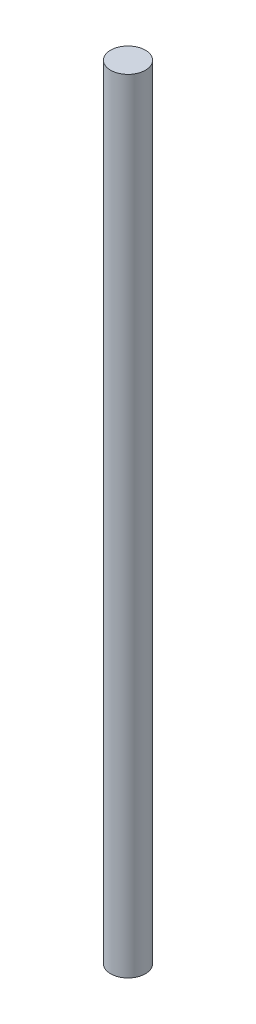
SolidWorks part; units mm, degrees
material "AISI 1045 Çelik, soğuk çekilmiş"
ref_plane "Ön Düzlem" through (0, 0, 0) normal (0, 0, 1) x (1, 0, 0)
ref_plane "Üst Düzlem" through (0, 0, 0) normal (0, 1, 0) x (1, 0, 0)
ref_plane "Sağ Düzlem" through (0, 0, 0) normal (1, 0, 0) x (0, 0, -1)
sketch "Çizim1" plane through (0, 0, 0) normal (0, 1, 0) x (1, 0, 0)
  circle A0 centre (0, 0) radius 2
  dimension "D1" = 4
extrude "Yükseklik-Ekstrüzyon1" add sketch "Çizim1" along normal blind 90
